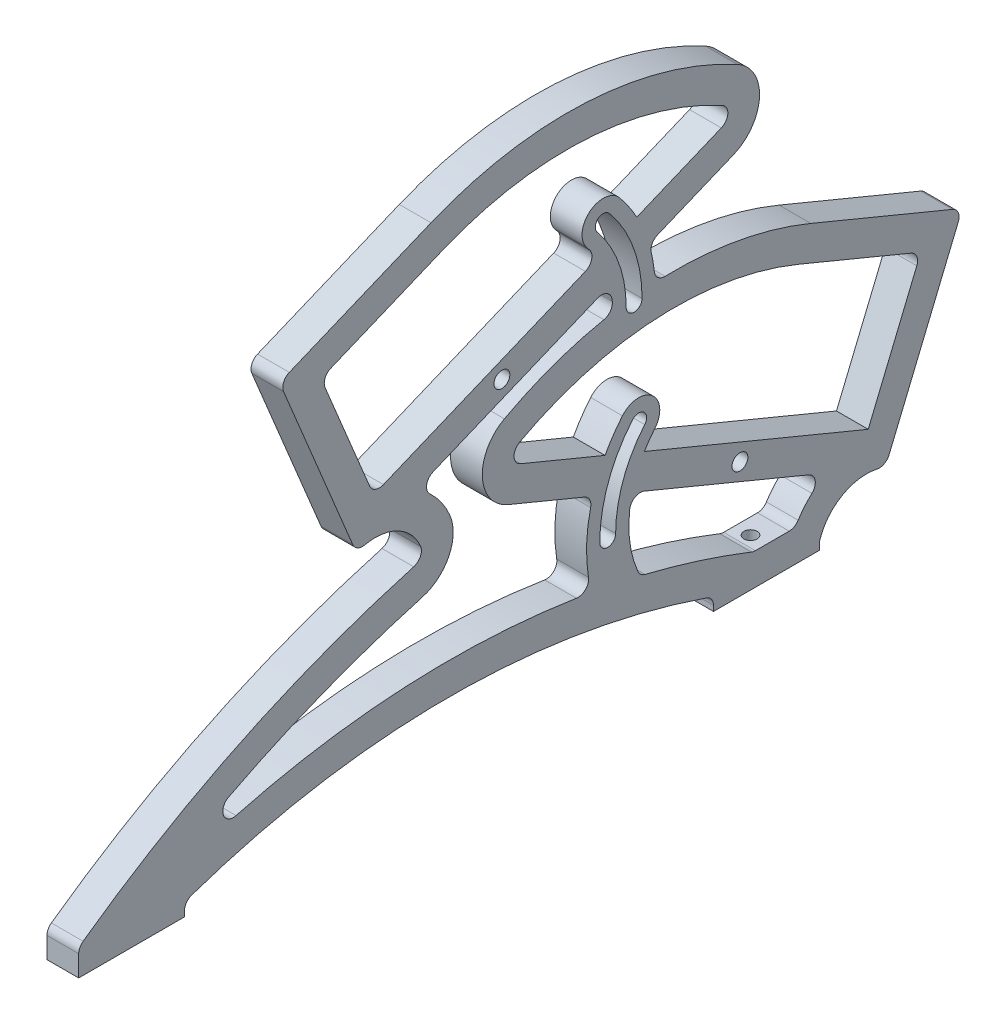
SolidWorks part; units mm, degrees
material "1060 Alloy"
ref_plane "Front Plane" through (0, 0, 0) normal (0, 0, 1) x (1, 0, 0)
ref_plane "Top Plane" through (0, 0, 0) normal (0, 1, 0) x (1, 0, 0)
ref_plane "Right Plane" through (0, 0, 0) normal (1, 0, 0) x (0, 0, -1)
sketch "Sketch1" plane through (0, 0, 0) normal (1, 0, 0) x (0, 0, -1)
  line L0 (0, 0) -> (0, 5)
  line L1 (38.8897, 78.8553) -> (54.5797, 40.9762) construction
  line L2 (38.8897, 78.8553) -> (112.8001, 109.47) construction
  line L3 (54.5797, 40.9762) -> (128.4901, 71.5909) construction
  line L4 (41.8855, 76.849) -> (54.1314, 47.2849) construction
  line L5 (112.8001, 109.47) -> (128.4901, 71.5909) construction
  line L6 (20, 1) -> (20, 0)
  line L7 (0, 0) -> (20, 0)
  line L8 (54.1314, 47.2849) -> (122.6217, 75.6545) construction
  line L9 (67.7541, 87.5641) -> (41.8855, 76.849) construction
  line L10 (80, 58) -> (105, 58) construction
  line L11 (99.1511, 74.0697) -> (80, 58) construction
  line L12 (100, 22) -> (125, 22) construction
  line L13 (125, 22) -> (105.8489, 38.0697) construction
  line L14 (166.1103, 42.8553) -> (150.4203, 4.9762) construction
  line L15 (166.1103, 42.8553) -> (92.1999, 73.47) construction
  line L16 (150.4203, 4.9762) -> (76.5099, 35.5909) construction
  line L17 (92.1999, 73.47) -> (76.5099, 35.5909) construction
  line L18 (150.8686, 11.2849) -> (163.1145, 40.849) construction
  line L19 (163.1145, 40.849) -> (137.2459, 51.5641) construction
  line L20 (82.3783, 39.6545) -> (150.8686, 11.2849) construction
  line L22 (105.5007, 71.8099) -> (121.4736, 78.4261)
  line L23 (152.4922, 7.3652) -> (167.0342, 42.4726)
  line L25 (66.6061, 90.3358) -> (37.9658, 78.4726)
  line L26 (37.9658, 78.4726) -> (52.5078, 43.3652)
  line L27 (63.7245, 48.0113) -> (100.3505, 63.1823)
  line L28 (140, 0) -> (140, 1)
  line L29 (152.4922, 7.3652) -> (143.6238, 11.0386) construction
  line L30 (98.0544, 68.7256) -> (55.755, 51.2046)
  line L31 (55.755, 51.2046) -> (45.8052, 75.2254)
  line L32 (45.8052, 75.2254) -> (68.9022, 84.7925)
  line L33 (106.9456, 32.7256) -> (149.245, 15.2046)
  line L34 (149.245, 15.2046) -> (159.1948, 39.2254)
  line L35 (159.1948, 39.2254) -> (136.0978, 48.7925)
  line L36 (56.0604, 34.7884) -> (62.7895, 37.5756) construction
  line L37 (52.5078, 43.3652) -> (58.8317, 45.9846) construction
  line L38 (104.6495, 27.1823) -> (141.2755, 12.0113)
  line L39 (135.4645, 6) -> (127.5413, 6)
  line L40 (123.7697, 72.8828) -> (107.7968, 66.2666)
  line L42 (167.0342, 42.4726) -> (138.3939, 54.3358)
  line L43 (140, 0) -> (120, 0)
  line L44 (81.2303, 36.8828) -> (97.2032, 30.2666)
  line L45 (99.4993, 35.8099) -> (83.5264, 42.4261)
  line L56 (120, 1) -> (120, 0)
  line L63 (174.6584, 96) -> (-14.1241, 96) construction
  circle A0 centre (80, 58) radius 1.5
  circle A1 centre (125, 22) radius 1.5
  arc A2 (99.1511, 74.0697) -> (105, 58) centre (80, 58) cw construction
  arc A3 (106.5, 58) -> (100.3002, 75.0339) centre (80, 58) ccw
  arc A4 (103.5, 58) -> (98.002, 73.1055) centre (80, 58) ccw
  arc A5 (103.5, 58) -> (106.5, 58) centre (105, 58) ccw
  arc A6 (100.3002, 75.0339) -> (98.002, 73.1055) centre (99.1511, 74.0697) ccw
  arc A7 (105.8489, 38.0697) -> (100, 22) centre (125, 22) ccw construction
  arc A8 (104.6998, 39.0339) -> (98.5, 22) centre (125, 22) ccw
  arc A9 (106.998, 37.1055) -> (101.5, 22) centre (125, 22) ccw
  arc A10 (106.998, 37.1055) -> (104.6998, 39.0339) centre (105.8489, 38.0697) ccw
  arc A11 (98.5, 22) -> (101.5, 22) centre (100, 22) ccw
  arc A12 (124.5244, 87.305) -> (123.7697, 72.8828) centre (120.7083, 80.2739) cw
  arc A13 (122.6217, 75.6545) -> (123.0934, 84.6683) centre (120.7083, 80.2739) ccw construction
  arc A14 (123.0934, 84.6683) -> (67.7541, 87.5641) centre (92.3875, 28.0938) ccw construction
  arc A15 (137.2459, 51.5641) -> (81.9066, 48.6683) centre (112.6125, -7.9062) ccw construction
  arc A16 (81.9066, 48.6683) -> (82.3783, 39.6545) centre (84.2917, 44.2739) ccw construction
  arc A17 (121.6623, 82.0317) -> (121.4736, 78.4261) centre (120.7083, 80.2739) cw
  arc A18 (138.3939, 54.3358) -> (108.9678, 59.3654) centre (112.6125, -7.9062) ccw
  arc A19 (107.7968, 66.2666) -> (108.9678, 59.3654) centre (80, 58) cw
  arc A20 (100.3505, 63.1823) -> (100.9951, 58.4548) centre (80, 58) cw
  arc A21 (124.5244, 87.305) -> (66.6061, 90.3358) centre (92.3875, 28.0938) ccw
  arc A22 (100.9951, 58.4548) -> (80.4756, 51.305) centre (112.6125, -7.9062) ccw
  arc A23 (80.4756, 51.305) -> (81.2303, 36.8828) centre (84.2917, 44.2739) ccw
  arc A24 (152.4922, 7.3652) -> (140.0944, 1.6073) centre (148.9396, -1.2116) ccw
  arc A25 (140.0944, 1.6073) -> (140, 1) centre (142, 1) ccw
  arc A26 (20, 1) -> (21.3514, 2.8919) centre (22, 1) cw
  arc A27 (52.5078, 43.3652) -> (64.6372, 38.341) centre (56.0604, 34.7884) cw
  arc A28 (68.9022, 84.7925) -> (121.6623, 82.0317) centre (92.3875, 28.0938) cw
  arc A31 (105.5007, 71.8099) -> (102.2153, 76.6408) centre (80, 58) ccw
  arc A32 (102.2153, 76.6408) -> (96.0869, 71.4985) centre (99.1511, 74.0697) ccw
  arc A33 (96.0869, 71.4985) -> (98.0544, 68.7256) centre (80, 58) cw
  arc A35 (136.0978, 48.7925) -> (83.3377, 46.0317) centre (112.6125, -7.9062) ccw
  arc A37 (83.3377, 46.0317) -> (83.5264, 42.4261) centre (84.2917, 44.2739) ccw
  arc A40 (99.4993, 35.8099) -> (102.7847, 40.6408) centre (125, 22) cw
  arc A41 (102.7847, 40.6408) -> (108.9131, 35.4985) centre (105.8489, 38.0697) cw
  arc A43 (108.9131, 35.4985) -> (106.9456, 32.7256) centre (125, 22) ccw
  arc A44 (120, 1) -> (118.6486, 2.8919) centre (118, 1) ccw
  arc A45 (118.6486, 2.8919) -> (21.3514, 2.8919) centre (70, -139) ccw
  arc A46 (64.6372, 38.341) -> (63.3305, 35.6502) centre (62.7895, 37.5756) cw
  arc A47 (63.3305, 35.6502) -> (0, 5) centre (117.4338, -156.8929) ccw
  arc A48 (97.2032, 30.2666) -> (96.9455, 14.6553) centre (125, 22) ccw
  arc A49 (96.9455, 14.6553) -> (11.4386, 5.591) centre (70, -139) ccw
  arc A50 (11.4386, 5.591) -> (64.9536, 29.8739) centre (117.4338, -156.8929) cw
  arc A51 (63.7245, 48.0113) -> (70.1805, 40.6371) centre (56.0604, 34.7884) cw
  arc A52 (64.9536, 29.8739) -> (70.1805, 40.6371) centre (62.7895, 37.5756) ccw
  arc A53 (104.6495, 27.1823) -> (106.1445, 12.755) centre (125, 22) ccw
  arc A54 (106.1445, 12.755) -> (127.5413, 6) centre (70, -139) cw
  arc A55 (141.2755, 12.0113) -> (135.4645, 6) centre (148.9396, -1.2116) ccw
  point P17 (103.4923, 66.5505)
  point P22 (101.5077, 30.5505)
  dimension "D1" = 3
  dimension "D3" = 1.5
  dimension "D8" = 5
  dimension "D11" = 22
  dimension "D12" = 80
  dimension "D14" = 22.5
  dimension "D16" = 2
  dimension "D17" = 6
  dimension "D21" = 30
  dimension "D22" = 35
  dimension "D23" = 80
  dimension "D24" = 3
  dimension "D18" = 6
  dimension "D29" = 58
  dimension "D25" = 5
  dimension "D28" = 2
  dimension "D47" = 4
  dimension "D48" = 4
  dimension "D49" = 3
  dimension "D54" = 4
  dimension "D55" = 4
  dimension "D56" = 2
  dimension "D57" = 150
  dimension "D58" = 2
  dimension "D59" = 200
  dimension "D60" = 6
  dimension "D61" = 6
  dimension "D62" = 4
  dimension "D63" = 6
  dimension "D64" = 8
  dimension "D67" = 4
  dimension "D68" = 6
  dimension "D69" = 6
  dimension "D19" = 25
  dimension "D2" = 25
  dimension "D4" = 25
  dimension "D5" = 40
  dimension "D6" = 40
  dimension "D7" = 125
  dimension "D9" = 20
  dimension "D10" = 100
  dimension "D13" = 1
  dimension "D15" = 22.5
  dimension "D20" = 30
  dimension "D26" = 3
  dimension "D27" = 2
  dimension "D30" = 3
  dimension "D32" = 96
  dimension "D33" = 3
  dimension "D34" = 3
  dimension "D35" = 3
  dimension "D41" = 3
  dimension "D42" = 3
  dimension "D43" = 3
  dimension "D44" = 3
  dimension "D50" = 3
  dimension "D51" = 3
  dimension "D65" = 6
  dimension "D66" = 3
extrude "Boss-Extrude1" add sketch "Sketch1" along normal blind 6
fillet "Fillet1" radius 2 22 edges at (3, 14.6553, -96.9455) (3, 27.1823, -104.6495) (3, 12.755, -106.1445) (3, 12.0113, -141.2755) (3, 6, -135.4645) (3, 6, -127.5413) (3, 39.2254, -159.1948) (3, 7.3652, -152.4922) (3, 51.2046, -55.755) (3, 78.4726, -37.9658) (3, 75.2254, -45.8052) (3, 43.3652, -52.5078) (3, 48.0113, -63.7245) (3, 5.591, -11.4386) (3, 5, 0) (3, 30.2666, -97.2032) (3, 58.4548, -100.9951) (3, 59.3654, -108.9678) (3, 66.2666, -107.7968) (3, 68.7256, -98.0544) (3, 63.1823, -100.3505) (3, 42.4726, -167.0342)
hole_wizard "Tap Drill for M3 Tap1" positions "Sketch3" profile "Sketch2" hole size "M3" standard "ISO"
sketch "Sketch3" plane through (0, 0, 0) normal (0, -1, 0) x (-1, 0, 0)
  line L0 (-6, 20) -> (0, 20) construction
  line L1 (0, 0) -> (0, 20) construction
  line L2 (-6, 120) -> (0, 120) construction
  point P0 (-3, 10)
  point P2 (-3, 130)
  dimension "D1" = 10
  dimension "D2" = 3
  dimension "D3" = 10
sketch "Sketch2" plane through (3, 0, -10) normal (1, 0, 0) x (0, 0, -1)
  line L0 (0, 0) -> (0, 10.7511)
  line L1 (0, 10.7511) -> (1.25, 10)
  line L2 (1.25, 10) -> (1.25, 0)
  line L5 (1.25, 0) -> (0, 0)
  line L10 (0, 10.7511) -> (-1.25, 10) construction
  line L11 (0, -6.35) -> (0, 107.95) construction
  dimension "Hole Dia." = 2.5
  dimension "Hole Depth" = 10
  dimension "Drill Angle" = 118
equation "\"ˇ35\"=76.24"
